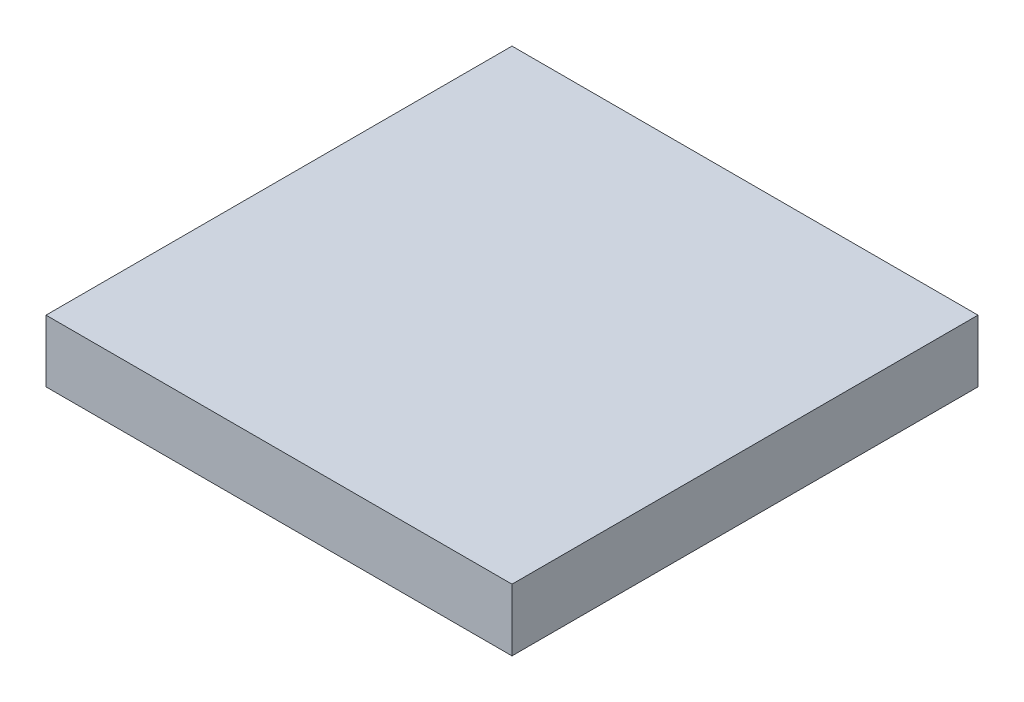
SolidWorks part; units mm, degrees
ref_plane "Front Plane" through (0, 0, 0) normal (0, 0, 1) x (1, 0, 0)
ref_plane "Top Plane" through (0, 0, 0) normal (0, 1, 0) x (1, 0, 0)
ref_plane "Right Plane" through (0, 0, 0) normal (1, 0, 0) x (0, 0, -1)
sketch "Sketch1" plane through (0, 0, 0) normal (0, 1, 0) x (1, 0, 0)
  line L1 (-7.6076, 7.4193) -> (7.3924, 7.4193)
  line L2 (-7.6076, 7.4193) -> (-7.6076, -7.5807)
  line L3 (-7.6076, -7.5807) -> (7.3924, -7.5807)
  line L4 (7.3924, 7.4193) -> (7.3924, -7.5807)
  line L5 (-7.6076, 7.4193) -> (7.3924, -7.5807) construction
  line L6 (-7.6076, -7.5807) -> (7.3924, 7.4193) construction
  point P0 (-0.1076, -0.0807)
  dimension "D1" = 15
  dimension "D2" = 15
extrude "Boss-Extrude1" add sketch "Sketch1" along normal blind 2
sketch "Sketch4" plane through (0, 0, 0) normal (0, 1, 0) x (1, 0, 0)
  line L0 (7.3924, 7.4193) -> (-7.6076, -7.5807) construction
  line L1 (7.3924, -7.5807) -> (-7.6076, 7.4193) construction
  line L2 (3.3924, -0.0807) -> (-3.6076, -0.0807) construction
  line L3 (7.3924, 7.4193) -> (-7.6076, 7.4193) construction
  line L5 (4.1924, 1.4193) -> (2.5924, 1.4193)
  line L6 (4.1924, 1.4193) -> (4.1924, -1.5807)
  line L7 (4.1924, -1.5807) -> (2.5924, -1.5807)
  line L8 (2.5924, 1.4193) -> (2.5924, -1.5807)
  line L9 (4.1924, 1.4193) -> (2.5924, -1.5807) construction
  line L10 (4.1924, -1.5807) -> (2.5924, 1.4193) construction
  line L11 (-2.8076, 1.4193) -> (-4.4076, 1.4193)
  line L12 (-2.8076, 1.4193) -> (-2.8076, -1.5807)
  line L13 (-2.8076, -1.5807) -> (-4.4076, -1.5807)
  line L14 (-4.4076, 1.4193) -> (-4.4076, -1.5807)
  line L15 (-2.8076, 1.4193) -> (-4.4076, -1.5807) construction
  line L16 (-2.8076, -1.5807) -> (-4.4076, 1.4193) construction
  point P11 (-0.1076, -0.0807)
  dimension "D1" = 7
  dimension "D2" = 3
  dimension "D3" = 1.6
  dimension "D4" = 3
  dimension "D5" = 1.6
extrude "Boss-Extrude2" add sketch "Sketch4" against normal blind 2
